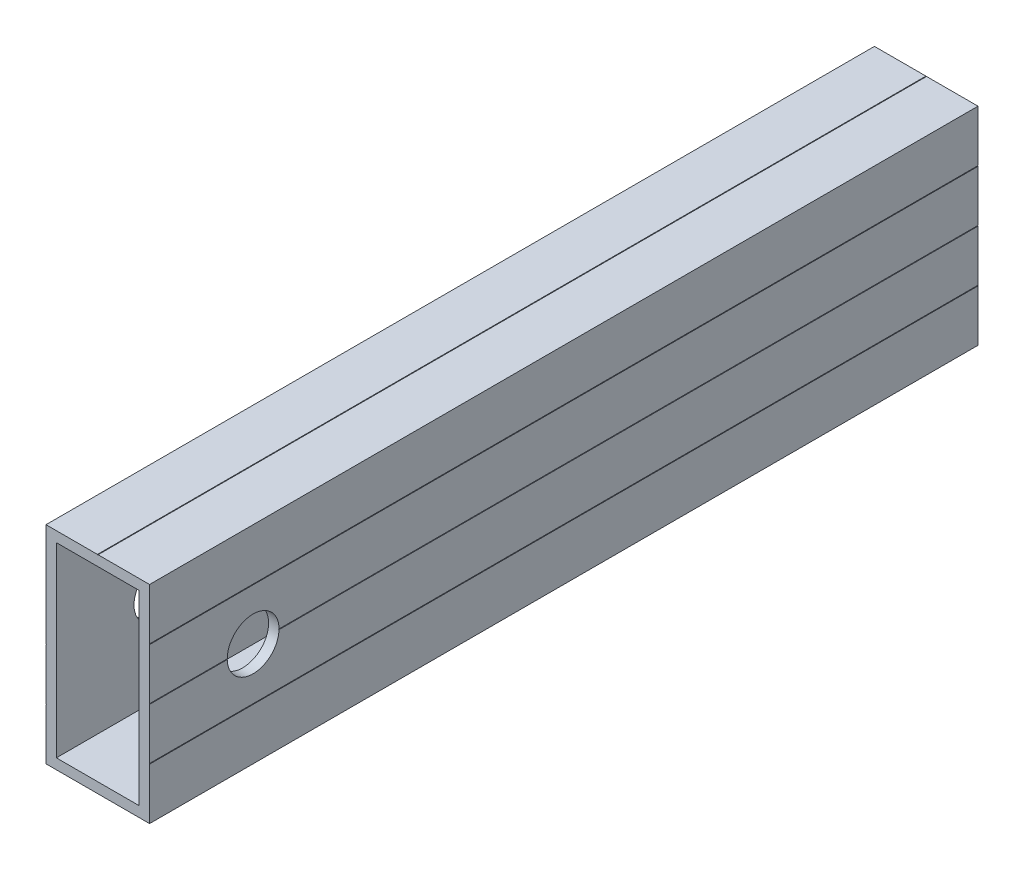
SolidWorks part; units mm, degrees
ref_plane "Front Plane" through (0, 0, 0) normal (0, 0, 1) x (1, 0, 0)
ref_plane "Top Plane" through (0, 0, 0) normal (0, 1, 0) x (1, 0, 0)
ref_plane "Right Plane" through (0, 0, 0) normal (1, 0, 0) x (0, 0, -1)
ref_plane "Plane1" through (12.7, 0, 0) normal (1, 0, 0) x (0, 0, -1)
sketch "Sketch1" plane through (12.7, 0, 0) normal (1, 0, 0) x (0, 0, -1)
  line L0 (-749.3, 25.4) -> (-749.3, -25.4)
  line L1 (-749.3, -25.4) -> (749.3, -25.4)
  line L2 (749.3, -25.4) -> (749.3, 25.4)
  line L3 (749.3, 25.4) -> (-749.3, 25.4)
extrude "Boss-Extrude1" add sketch "Sketch1" against normal blind 25.4
sketch "Sketch2" plane through (0, 0, 749.3) normal (0, 0, 1) x (1, 0, 0)
  line L0 (0.0762, 25.4) -> (-0.0762, 25.4)
  line L1 (-0.0762, 25.4) -> (0.0762, 25.2476)
  line L2 (0.0762, 25.2476) -> (0.0762, 25.4)
extrude "Cut-Extrude1" cut sketch "Sketch2" against normal blind 1498.6
sketch "Sketch3" plane through (0, 0, 749.3) normal (0, 0, 1) x (1, 0, 0)
  line L0 (12.7, 12.6238) -> (12.7, 12.7762)
  line L1 (12.7, 12.7762) -> (12.5476, 12.7762)
  line L2 (12.5476, 12.7762) -> (12.7, 12.6238)
extrude "Cut-Extrude2" cut sketch "Sketch3" against normal through all
sketch "Sketch4" plane through (0, 0, 749.3) normal (0, 0, 1) x (1, 0, 0)
  line L0 (12.7, -0.0762) -> (12.7, 0.0762)
  line L1 (12.7, 0.0762) -> (12.5476, -0.0762)
  line L2 (12.5476, -0.0762) -> (12.7, -0.0762)
extrude "Cut-Extrude3" cut sketch "Sketch4" against normal blind 1498.6
sketch "Sketch5" plane through (0, 0, 749.3) normal (0, 0, 1) x (1, 0, 0)
  line L0 (12.7, -12.7762) -> (12.7, -12.6238)
  line L1 (12.7, -12.6238) -> (12.5476, -12.6238)
  line L2 (12.5476, -12.6238) -> (12.7, -12.7762)
extrude "Cut-Extrude4" cut sketch "Sketch5" against normal blind 1498.6
sketch "Sketch6" plane through (0, 0, 749.3) normal (0, 0, 1) x (1, 0, 0)
  line L0 (0.0762, -25.4) -> (-0.0762, -25.2476)
  line L1 (-0.0762, -25.2476) -> (-0.0762, -25.4)
  line L2 (-0.0762, -25.4) -> (0.0762, -25.4)
extrude "Cut-Extrude5" cut sketch "Sketch6" against normal through all
sketch "Sketch7" plane through (0, 0, 749.3) normal (0, 0, 1) x (1, 0, 0)
  line L0 (-12.7, -12.6238) -> (-12.7, -12.7762)
  line L1 (-12.7, -12.7762) -> (-12.5476, -12.7762)
  line L2 (-12.5476, -12.7762) -> (-12.7, -12.6238)
extrude "Cut-Extrude6" cut sketch "Sketch7" against normal through all
sketch "Sketch8" plane through (0, 0, 749.3) normal (0, 0, 1) x (1, 0, 0)
  line L0 (-12.7, 0.0762) -> (-12.7, -0.0762)
  line L1 (-12.7, -0.0762) -> (-12.5476, 0.0762)
  line L2 (-12.5476, 0.0762) -> (-12.7, 0.0762)
extrude "Cut-Extrude7" cut sketch "Sketch8" against normal blind 1498.6
sketch "Sketch9" plane through (0, 0, 749.3) normal (0, 0, 1) x (1, 0, 0)
  line L0 (-12.7, 12.7762) -> (-12.7, 12.6238)
  line L1 (-12.7, 12.6238) -> (-12.5476, 12.6238)
  line L2 (-12.5476, 12.6238) -> (-12.7, 12.7762)
extrude "Cut-Extrude8" cut sketch "Sketch9" against normal blind 1498.6
sketch "Sketch10" plane through (0, 0, 749.3) normal (0, 0, 1) x (1, 0, 0)
  line L0 (10.16, -22.86) -> (10.16, 22.86)
  line L1 (10.16, 22.86) -> (-10.16, 22.86)
  line L2 (-10.16, 22.86) -> (-10.16, -22.86)
  line L3 (-10.16, -22.86) -> (10.16, -22.86)
extrude "Cut-Extrude9" cut sketch "Sketch10" against normal through all
draft "Draft1" type of draft neutral plane draft angle 45 faces to draft 1 face at (0.0762, 25.3238, 0) neutral plane through (-12.7, 25.4, -749.3) neutral plane normal (0, 1, 0) parameters "D1"=45
draft "Draft2" type of draft neutral plane draft angle 45 faces to draft 1 face at (12.6238, 12.7762, 0) neutral plane through (12.7, 0, 0) neutral plane normal (1, 0, 0) parameters "D1"=45
draft "Draft3" type of draft neutral plane draft angle 45 faces to draft 1 face at (-0.0762, -25.3238, 0) neutral plane through (-12.7, -25.4, 749.3) neutral plane normal (0, -1, 0) parameters "D1"=45
draft "Draft4" type of draft neutral plane draft angle 45 faces to draft 1 face at (-12.6238, -12.7762, 0) neutral plane through (-12.7, 0, 0) neutral plane normal (-1, 0, 0) parameters "D1"=45
draft "Draft5" type of draft neutral plane draft angle 45 faces to draft 2 face at (12.6238, -12.6238, 0) face at (12.6238, 0, 0) neutral plane through (12.7, 0, 0) neutral plane normal (1, 0, 0) parameters "D1"=45
draft "Draft6" type of draft neutral plane draft angle 45 faces to draft 2 face at (-12.6238, 0, 0) face at (-12.6238, 12.6238, 0) neutral plane through (-12.7, 0, 0) neutral plane normal (-1, 0, 0) parameters "D1"=45
sketch "Sketch11" plane through (0, 0, -749.3) normal (0, 0, -1) x (-1, 0, 0)
  line L1 (28.0564, 44.6652) -> (-33.9059, 44.6652)
  line L2 (28.0564, 44.6652) -> (28.0564, -44.0138)
  line L3 (28.0564, -44.0138) -> (-33.9059, -44.0138)
  line L4 (-33.9059, 44.6652) -> (-33.9059, -44.0138)
extrude "Cut-Extrude10" cut sketch "Sketch11" against normal blind 1295.4
sketch "Sketch13" plane through (12.7, 0, 0) normal (1, 0, 0) x (0, 0, -1)
  line L0 (-546.1, 0.0762) -> (-749.3, 0.0762) construction
  line L2 (-749.3, 12.6238) -> (-749.3, 0.0762) construction
  circle A0 centre (-723.9, 0.0762) radius 6.35
  dimension "D1" = 12.7
  dimension "D2" = 25.4
extrude "Cut-Extrude11" cut sketch "Sketch13" against normal blind 25.4
